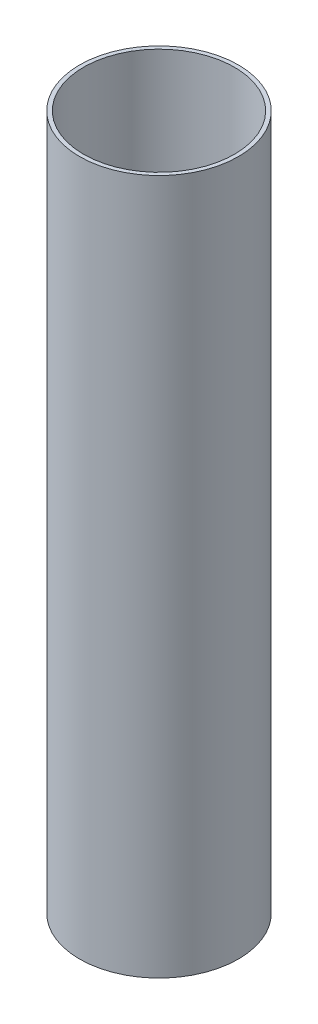
SolidWorks part; units mm, degrees
ref_plane "Front Plane" through (0, 0, 0) normal (0, 0, 1) x (1, 0, 0)
ref_plane "Top Plane" through (0, 0, 0) normal (0, 1, 0) x (1, 0, 0)
ref_plane "Right Plane" through (0, 0, 0) normal (1, 0, 0) x (0, 0, -1)
sketch "Sketch1" plane through (0, 0, 0) normal (0, 1, 0) x (1, 0, 0)
  circle A0 centre (0, 0) radius 40
  circle A1 centre (0, 0) radius 38
extrude "Boss-Extrude1" add sketch "Sketch1" along normal blind 350
